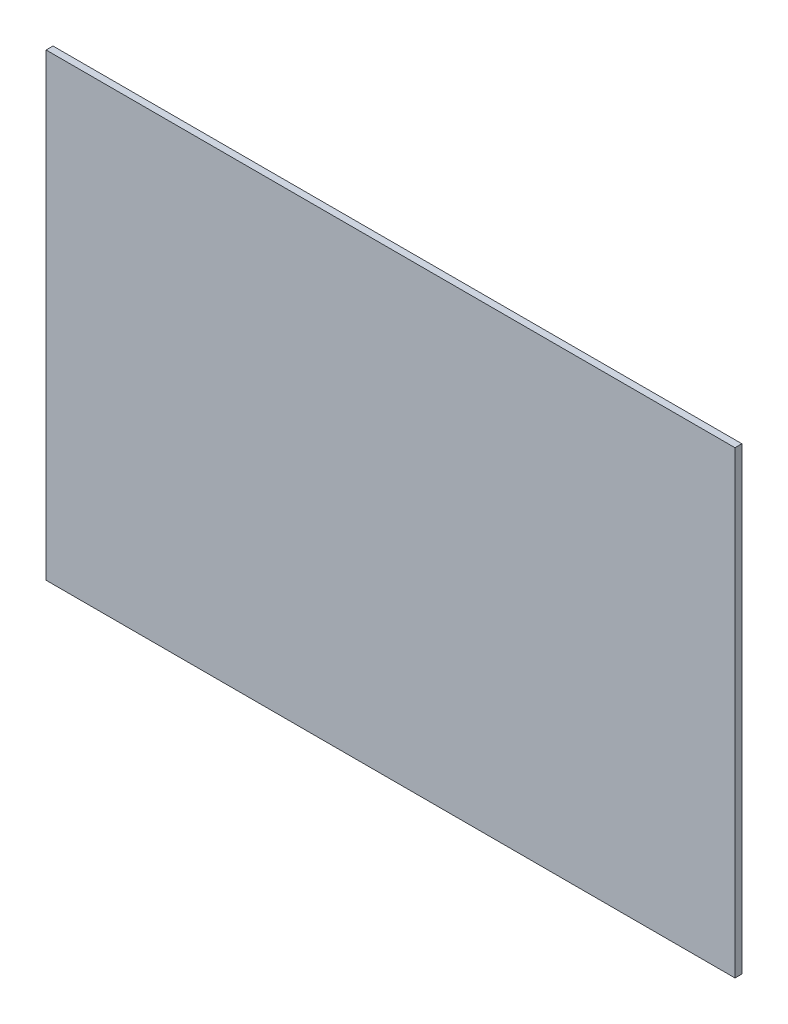
SolidWorks part; units mm, degrees
material "Лист 3,0 ГОСТ 19903-2015 / Ст3сп ГОСТ 14637-89"
ref_plane "Спереди" through (0, 0, 0) normal (0, 0, 1) x (1, 0, 0)
ref_plane "Сверху" through (0, 0, 0) normal (0, 1, 0) x (1, 0, 0)
ref_plane "Справа" through (0, 0, 0) normal (1, 0, 0) x (0, 0, -1)
sketch "Эскиз1" plane through (0, 0, 0) normal (0, 0, 1) x (1, 0, 0)
  line L1 (-150, -100) -> (150, -100)
  line L2 (-150, -100) -> (-150, 100)
  line L3 (-150, 100) -> (150, 100)
  line L4 (150, -100) -> (150, 100)
extrude "Бобышка-Вытянуть1" add sketch "Эскиз1" along normal blind 3
